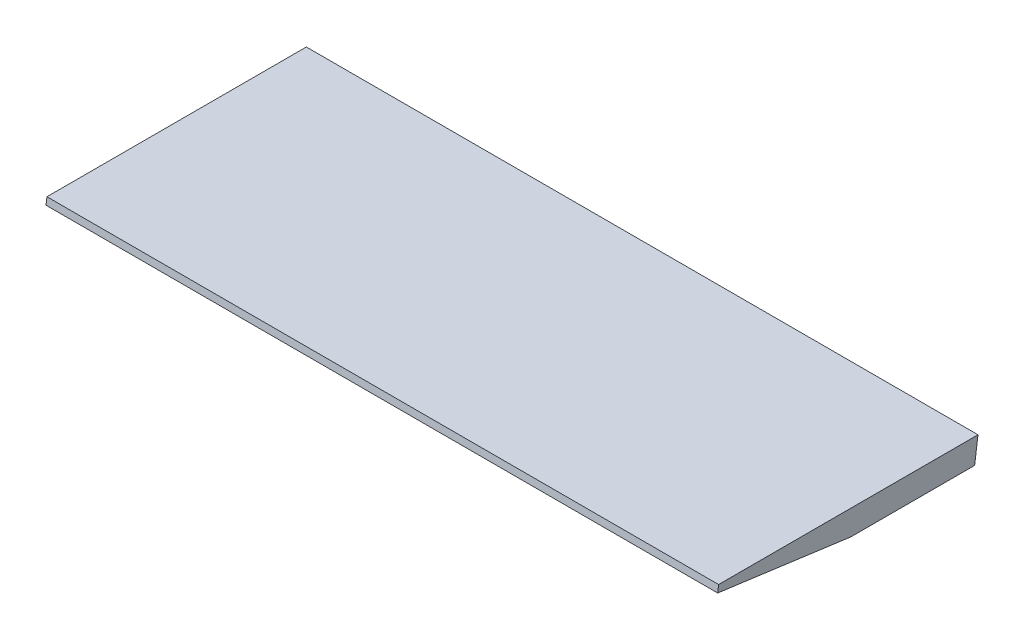
SolidWorks part; units mm, degrees
ref_plane "Front Plane" through (0, 0, 0) normal (0, 0, 1) x (1, 0, 0)
ref_plane "Top Plane" through (0, 0, 0) normal (0, 1, 0) x (1, 0, 0)
ref_plane "Right Plane" through (0, 0, 0) normal (1, 0, 0) x (0, 0, -1)
sketch "Sketch1" plane through (0, 0, 0) normal (0, 1, 0) x (1, 0, 0)
  line L1 (0, 0) -> (514.35, 0)
  line L2 (0, 0) -> (0, 203.2)
  line L3 (0, 203.2) -> (514.35, 203.2)
  line L4 (514.35, 0) -> (514.35, 203.2)
  line L5 (0, 0) -> (514.35, 203.2) construction
  line L6 (0, 203.2) -> (514.35, 0) construction
  point P4 (257.175, 101.6)
  dimension "D1" = 514.35
  dimension "D2" = 203.2
extrude "Boss-Extrude1" add sketch "Sketch1" along normal blind 19.05
sketch "Sketch5" plane through (514.35, 0, 0) normal (1, 0, 0) x (0, 0, -1)
  line L0 (0, 19.05) -> (4.5616, 19.05)
  line L1 (0, 19.05) -> (203.2, 19.05) construction
  line L2 (3.8482, 13.7697) -> (20.8517, 139.6263) construction
  line L3 (4.5616, 19.05) -> (3.8482, 13.7697)
  line L5 (0, 0) -> (203.2, 0) construction
  line L6 (-15.0302, 16.3202) -> (198.926, -12.5857) construction
  line L7 (105.769, 0) -> (0, 0)
  line L8 (0, 0) -> (0, 19.05)
  line L9 (203.2, 19.05) -> (200.6263, 0)
  line L10 (196.3755, -31.4641) -> (203.1768, 18.8785) construction
  line L11 (200.6263, 0) -> (203.2, 0)
  line L12 (203.2, 0) -> (203.2, 19.05)
  line L13 (3.8482, 13.7697) -> (105.769, 0)
extrude "Cut-Extrude3" cut sketch "Sketch5" against normal blind 781.6864
